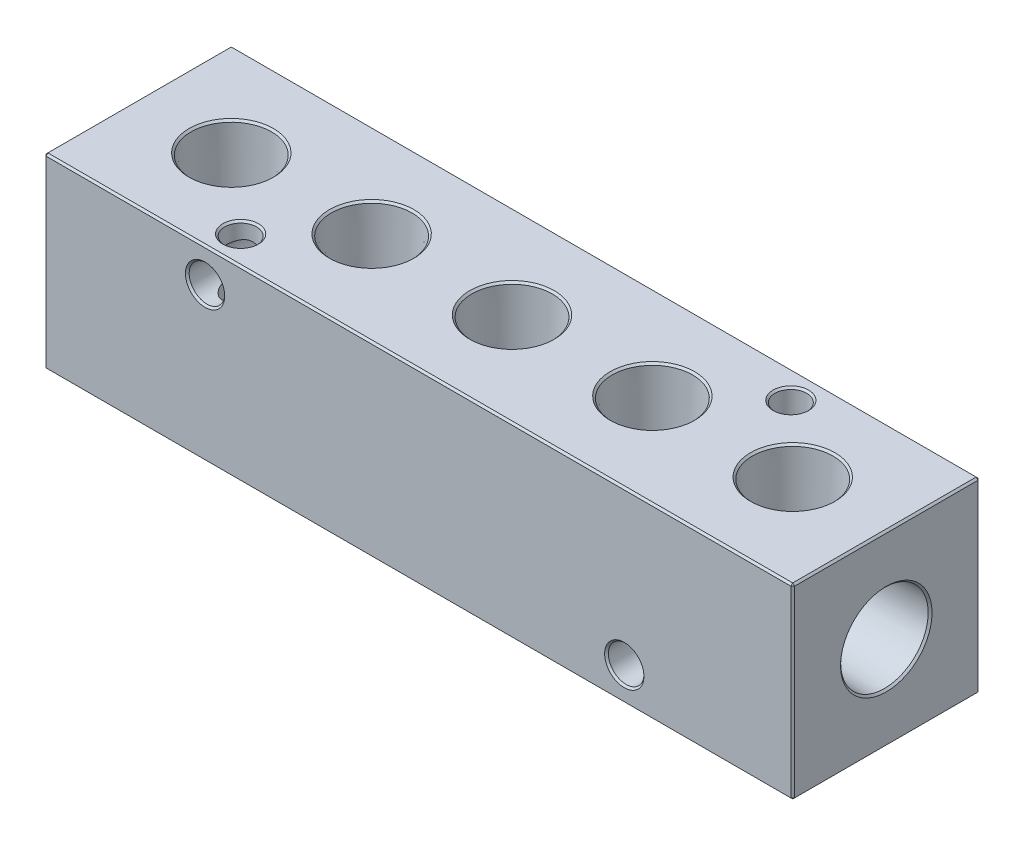
SolidWorks part; units mm, degrees
material "6061-T6 (SS)"
ref_plane "Front Plane" through (0, 0, 0) normal (0, 0, 1) x (1, 0, 0)
ref_plane "Top Plane" through (0, 0, 0) normal (0, 1, 0) x (1, 0, 0)
ref_plane "Right Plane" through (0, 0, 0) normal (1, 0, 0) x (0, 0, -1)
sketch "Sketch1" plane through (0, 0, 0) normal (1, 0, 0) x (0, 0, -1)
  line L1 (12.7, -12.7) -> (-12.7, -12.7)
  line L2 (12.7, -12.7) -> (12.7, 12.7)
  line L3 (12.7, 12.7) -> (-12.7, 12.7)
  line L4 (-12.7, -12.7) -> (-12.7, 12.7)
  line L5 (12.7, -12.7) -> (-12.7, 12.7) construction
  line L6 (12.7, 12.7) -> (-12.7, -12.7) construction
  circle A0 centre (0, 0) radius 5.5753
  point P0 (0, 0)
  dimension "D2" = 11.1506
  dimension "D1" = 25.4
extrude "Boss-Extrude1" add sketch "Sketch1" along normal mid plane 101.6
sketch "Sketch2" plane through (0, 0, 0) normal (0, 0, 1) x (1, 0, 0)
  line L0 (-38.1, 12.7) -> (-38.1, 0)
  line L1 (50.8, 12.7) -> (-50.8, 12.7) construction
  line L2 (-38.1, 0) -> (-43.18, 0)
  line L3 (-43.18, 0) -> (-43.5769, 12.7)
  line L4 (-43.5769, 12.7) -> (-38.1, 12.7)
  line L5 (-50.8, 12.7) -> (-50.8, -12.7) construction
  line L6 (-38.1, 0) -> (-38.1, -4.0166) construction
  dimension "D1" = 1.79
  dimension "D2" = 12.7
  dimension "D3" = 10.16
revolve "Cut-Revolve1" cut sketch "Sketch2" angle 360 about L0
pattern_linear "LPattern1" count 5 spacing 19.05 along (1, 0, 0) of "Cut-Revolve1"
sketch "Sketch3" plane through (0, 0, 0) normal (0, 0, 1) x (1, 0, 0)
  line L0 (-50.8, 5.9443) -> (-36.5125, 5.4978)
  line L1 (-50.8, 12.7) -> (-50.8, -12.7) construction
  line L2 (-36.5125, 5.4978) -> (-36.5125, 0)
  line L3 (-36.5125, 0) -> (-50.8, 0)
  line L4 (-50.8, 0) -> (-50.8, 5.9443)
  line L5 (-36.5125, 0) -> (-26.4621, 0) construction
  line L6 (50.8, 5.9443) -> (36.5125, 5.4978)
  line L7 (36.5125, 5.4978) -> (36.5125, 0)
  line L8 (36.5125, 0) -> (50.8, 0)
  line L9 (50.8, 0) -> (50.8, 5.9443)
  line L10 (50.8, -12.7) -> (50.8, 12.7) construction
  dimension "D1" = 1.79
  dimension "D2" = 10.9957
  dimension "D3" = 14.2875
revolve "Cut-Revolve2" cut sketch "Sketch3" angle 360 about L5
sketch "Sketch4" plane through (0, 12.7, 0) normal (0, 1, 0) x (1, 0, 0)
  line L0 (-50.8, 12.7) -> (-50.8, -12.7) construction
  line L1 (50.8, -12.7) -> (-50.8, -12.7) construction
  line L2 (50.8, 12.7) -> (-50.8, 12.7) construction
  line L3 (50.8, 12.7) -> (50.8, -12.7) construction
  circle A0 centre (-27.94, -8.89) radius 2.159
  circle A1 centre (28.956, 8.89) radius 2.159
  dimension "D1" = 4.318
  dimension "D2" = 22.86
  dimension "D3" = 3.81
  dimension "D4" = 3.81
  dimension "D5" = 21.844
extrude "Cut-Extrude1" cut sketch "Sketch4" against normal through all
sketch "Sketch5" plane through (0, 0, 12.7) normal (0, 0, 1) x (1, 0, 0)
  line L0 (-50.8, 12.7) -> (-50.8, -12.7) construction
  line L1 (50.8, 12.7) -> (50.8, -12.7) construction
  line L2 (50.8, -12.7) -> (-50.8, -12.7) construction
  line L3 (50.8, 12.7) -> (-50.8, 12.7) construction
  circle A0 centre (-28.956, 8.128) radius 2.413
  circle A1 centre (27.94, -8.128) radius 2.413
  dimension "D1" = 4.826
  dimension "D2" = 21.844
  dimension "D3" = 22.86
  dimension "D4" = 4.572
  dimension "D5" = 4.572
extrude "Cut-Extrude2" cut sketch "Sketch5" against normal through all
chamfer "Chamfer1" distance 0.254 angle 45 27 edges at (-50.8, -5.9443, 0) (30.353, -8.128, -12.7) (-26.543, 8.128, -12.7) (30.353, -8.128, 12.7) (-26.543, 8.128, 12.7) (28.956, -12.7, -6.731) (-27.94, -12.7, 11.049) (50.8, -5.9443, 0) (-50.8, 0, -12.7) (-50.8, 0, 12.7) (0, -12.7, 12.7) (-50.8, -12.7, 0) (0, -12.7, -12.7) (50.8, 0, -12.7) (50.8, -12.7, 0) (50.8, 0, 12.7) (0, 12.7, -12.7) (50.8, 12.7, 0) (0, 12.7, 12.7) (-50.8, 12.7, 0) (-38.1, 12.7, 5.4769) (-19.05, 12.7, 5.4769) (0, 12.7, 5.4769) (19.05, 12.7, 5.4769) (38.1, 12.7, 5.4769) (28.956, 12.7, -6.731) (-27.94, 12.7, 11.049)
